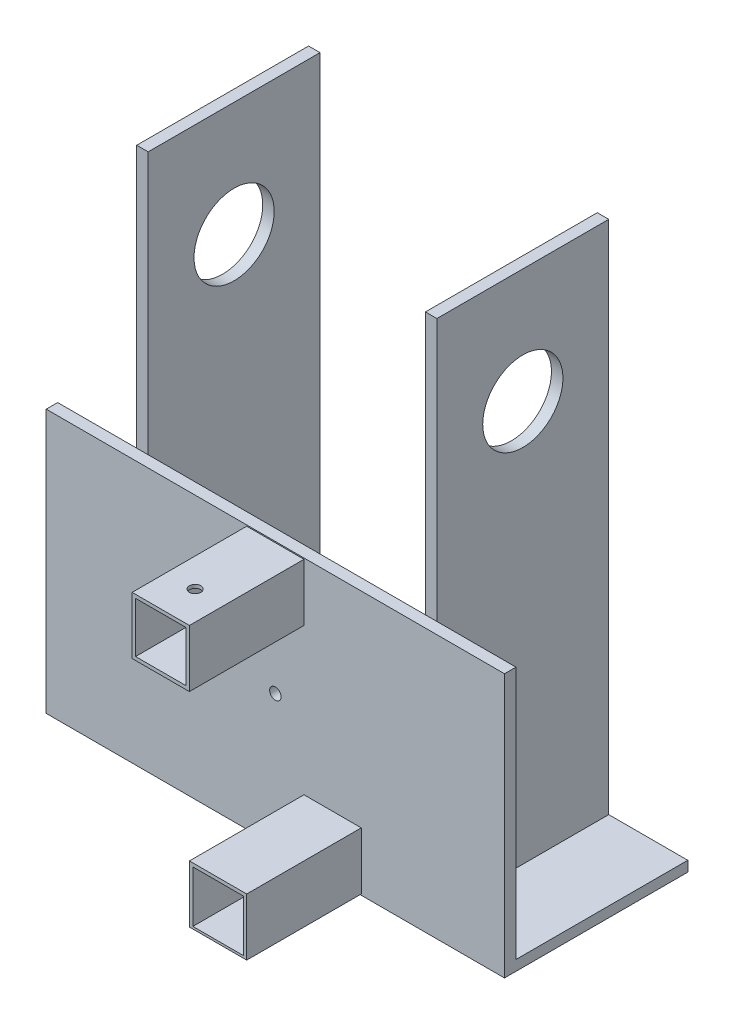
SolidWorks part; units mm, degrees
ref_plane "Plano frontal" through (0, 0, 0) normal (0, 0, 1) x (1, 0, 0)
ref_plane "Plano superior" through (0, 0, 0) normal (0, 1, 0) x (1, 0, 0)
ref_plane "Plano direito" through (0, 0, 0) normal (1, 0, 0) x (0, 0, -1)
sketch "Esboço1" plane through (0, 0, 0) normal (0, 1, 0) x (1, 0, 0)
  line L1 (-200, 75) -> (200, 75)
  line L2 (-200, 75) -> (-200, -75)
  line L3 (-200, -75) -> (200, -75)
  line L4 (200, 75) -> (200, -75)
  line L5 (-200, 75) -> (200, -75) construction
  line L6 (-200, -75) -> (200, 75) construction
  point P0 (0, 0)
  dimension "D1" = 400
  dimension "D2" = 150
extrude "Ressalto-extrusão1" add sketch "Esboço1" along normal blind 9
sketch "Esboço2" plane through (0, 9, 0) normal (0, 1, 0) x (1, 0, 0)
  line L0 (-126, 0) -> (126, 0) construction
  line L1 (-200, -75) -> (200, -75) construction
  line L2 (-131, 75) -> (-121, 75)
  line L3 (-131, 75) -> (-131, -75)
  line L4 (-131, -75) -> (-121, -75)
  line L5 (-121, 75) -> (-121, -75)
  line L6 (-131, 75) -> (-121, -75) construction
  line L7 (-131, -75) -> (-121, 75) construction
  line L8 (0, 75) -> (0, -75) construction
  line L9 (131, -75) -> (121, 75) construction
  line L10 (131, 75) -> (121, -75) construction
  line L11 (121, 75) -> (121, -75)
  line L12 (131, -75) -> (121, -75)
  line L13 (131, 75) -> (131, -75)
  line L14 (131, 75) -> (121, 75)
  point P4 (0, 0)
  point P14 (0, 0)
  dimension "D1" = 10
  dimension "D2" = 242
  dimension "D3" = 150
extrude "Ressalto-extrusão2" add sketch "Esboço2" along normal blind 450
sketch "Esboço5" plane through (-131, 0, 0) normal (-1, 0, 0) x (0, 0, 1)
  line L0 (-75, 459) -> (75, 459) construction
  circle A0 centre (0, 359) radius 35
  dimension "D2" = 70
  dimension "D1" = 100
extrude "Corte-extrusão1" cut sketch "Esboço5" against normal blind 300
sketch "Esboço6" plane through (0, 0, 0) normal (0, -1, 0) x (1, 0, 0)
  line L0 (-200, -75) -> (-200, 75) construction
  line L1 (200, 85) -> (-200, 85)
  line L2 (200, 85) -> (200, 75)
  line L3 (200, 75) -> (-200, 75)
  line L4 (-200, 85) -> (-200, 75)
  line L5 (200, 85) -> (-200, 75) construction
  line L6 (200, 75) -> (-200, 85) construction
  line L7 (200, 75) -> (200, -75) construction
  point P4 (0, 80)
  point P8 (0, 0)
  point P9 (0, 0)
  point P10 (-4.1573, 88.0225)
  point P11 (0, 0)
  dimension "D1" = 10
extrude "Ressalto-extrusão4" add sketch "Esboço6" against normal blind 230
ref_plane "Plano1" through (0, 0, 0) normal (-1, 0, 0) x (0, 0, 1)
sketch "Esboço8" plane through (0, 0, 0) normal (-1, 0, 0) x (0, 0, 1)
  line L5 (85, 179) -> (185, 179)
  line L6 (85, 179) -> (85, 229)
  line L7 (85, 230) -> (85, 0) construction
  line L12 (85, 229) -> (185, 229)
  line L13 (185, 179) -> (185, 229)
  line L14 (85, 230) -> (75, 230) construction
  line L15 (85, 179) -> (185, 229) construction
  line L16 (85, 229) -> (185, 179) construction
  point P4 (135, 204)
  point P5 (0, 0)
  dimension "D1" = 50
  dimension "D2" = 100
  dimension "D3" = 1
extrude "Ressalto-extrusão5" add sketch "Esboço8" against normal mid plane 50
sketch "Esboço9" plane through (0, 230, 0) normal (0, 1, 0) x (-1, 0, 0)
  line L0 (0, 75) -> (0, 185) construction
  line L1 (200, 75) -> (-200, 75) construction
  line L2 (-25, 185) -> (25, 185) construction
  circle A0 centre (0, 155) radius 5
  point P6 (0, 154.5)
  point P7 (0, 0)
  point P8 (1.9051, 140.686)
  point P9 (0, 0)
  point P12 (0, 75)
  point P13 (0, 0)
  point P14 (0, 0)
  point P17 (0, 185)
  point P18 (0, 125)
  point P19 (0, 0)
  dimension "D1" = 10
  dimension "D2" = 30
extrude "Corte-extrusão3" cut sketch "Esboço9" against normal blind 50
sketch "Esboço7" plane through (0, 0, 75) normal (0, 0, -1) x (-1, 0, 0)
  line L0 (0, 0) -> (0, 230) construction
  line L1 (200, 230) -> (-200, 230) construction
  circle A0 centre (0, 115) radius 5
  dimension "D1" = 10
extrude "Corte-extrusão2" cut sketch "Esboço7" against normal blind 150
ref_plane "Plano2" through (75, 0, 0) normal (-1, 0, 0) x (0, 0, 1)
sketch "Esboço11" plane through (75, 0, 0) normal (-1, 0, 0) x (0, 0, 1)
  line L1 (85, 51) -> (185, 51)
  line L2 (85, 51) -> (85, 1)
  line L3 (85, 1) -> (185, 1)
  line L4 (185, 51) -> (185, 1)
  line L5 (85, 51) -> (185, 1) construction
  line L6 (85, 1) -> (185, 51) construction
  line L7 (185, 179) -> (185, 229) construction
  line L8 (85, 230) -> (85, 0) construction
  line L12 (-75, 0) -> (85, 0) construction
  point P4 (135, 26)
  point P5 (0, 0)
  point P9 (0, 0)
  point P10 (0, 0)
  dimension "D1" = 1
extrude "Ressalto-extrusão6" add sketch "Esboço11" along normal blind 50
sketch "Esboço12" plane through (25, 0, 0) normal (-1, 0, 0) x (0, 0, 1)
  line L0 (185, 1) -> (185, 51) construction
  circle A0 centre (139.8111, 26) radius 5
  point P4 (185, 26)
  dimension "D1" = 10
extrude "Corte-extrusão4" cut sketch "Esboço12" against normal blind 30
sketch "Esboço13" plane through (0, 0, 185) normal (0, 0, 1) x (1, 0, 0)
  line L0 (-25, 229) -> (-25, 179) construction
  line L1 (72, 3) -> (28, 3)
  line L2 (72, 3) -> (72, 48)
  line L3 (72, 48) -> (28, 48)
  line L4 (28, 3) -> (28, 48)
  line L5 (72, 3) -> (28, 48) construction
  line L6 (72, 48) -> (28, 3) construction
  line L7 (22, 226) -> (-22, 226)
  line L8 (22, 226) -> (22, 182)
  line L9 (22, 182) -> (-22, 182)
  line L10 (-22, 226) -> (-22, 182)
  line L11 (22, 226) -> (-22, 182) construction
  line L12 (22, 182) -> (-22, 226) construction
  line L13 (25, 179) -> (-25, 179) construction
  line L14 (25, 229) -> (-25, 229) construction
  line L15 (25, 179) -> (25, 229) construction
  line L16 (25, 1) -> (25, 51) construction
  line L17 (25, 51) -> (75, 51) construction
  line L18 (-200, 0) -> (200, 0) construction
  line L19 (75, 1) -> (75, 51) construction
  point P0 (50, 25.5)
  point P5 (0, 204)
  dimension "D1" = 3
  dimension "D2" = 3
  dimension "D3" = 3
  dimension "D4" = 3
  dimension "D5" = 3
  dimension "D6" = 3
  dimension "D7" = 3
  dimension "D8" = 3
extrude "Corte-extrusão5" cut sketch "Esboço13" against normal up to surface (100 mm away) up to face at (50, 26, 85)
sketch "Esboço14" plane through (0, 0, 85) normal (0, 0, 1) x (1, 0, 0)
  line L0 (22, 226) -> (-22, 182) construction
  line L1 (72, 48) -> (28, 3) construction
  circle A0 centre (0, 204) radius 5
  circle A1 centre (50, 25.5) radius 5
  point P12 (0, 0)
  point P13 (0, 0)
  point P14 (0, 0)
  dimension "D1" = 10
extrude "Corte-extrusão6" cut sketch "Esboço14" against normal blind 10
